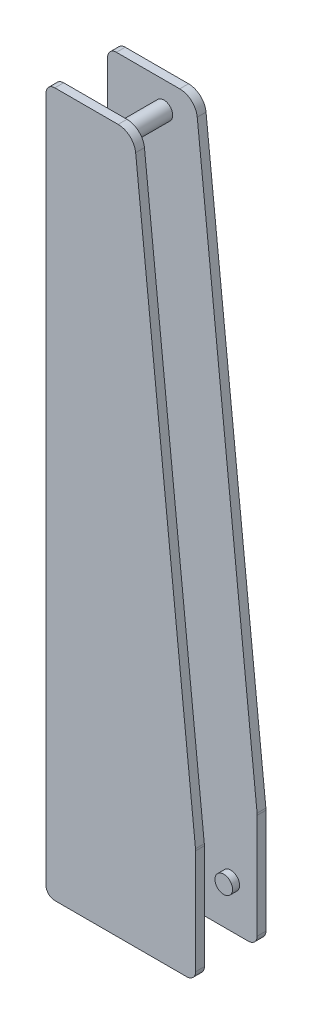
SolidWorks part; units mm, degrees
ref_plane "Front Plane" through (0, 0, 0) normal (0, 0, 1) x (1, 0, 0)
ref_plane "Top Plane" through (0, 0, 0) normal (0, 1, 0) x (1, 0, 0)
ref_plane "Right Plane" through (0, 0, 0) normal (1, 0, 0) x (0, 0, -1)
sketch "Sketch2" plane through (0, 0, 0) normal (0, 0, 1) x (1, 0, 0)
  line L0 (0.9362, 291.0391) -> (34.9459, -34.4819)
  line L1 (-45, 300) -> (-9.0097, 300)
  line L2 (-50, 295) -> (-50, -95)
  line L3 (-45, -100) -> (30, -100)
  line L4 (35, -35.521) -> (35, -95)
  arc A0 (30, -100) -> (35, -95) centre (30, -95) ccw
  arc A1 (-50, -95) -> (-45, -100) centre (-45, -95) ccw
  arc A3 (-45, 300) -> (-50, 295) centre (-45, 295) ccw
  arc A4 (34.9459, -34.4819) -> (35, -35.521) centre (25, -35.521) cw
  arc A5 (0.9362, 291.0391) -> (-9.0097, 300) centre (-9.0097, 290) ccw
  point P10 (35, -35)
  point P17 (0, 300)
  dimension "D5" = 5
  dimension "D8" = 10
  dimension "D1" = 400
  dimension "D2" = 85
  dimension "D3" = 100
  dimension "D4" = 35
  dimension "D6" = 50
  dimension "D7" = 35
extrude "Boss-Extrude1" add sketch "Sketch2" along normal blind 5
sketch "Sketch3" plane through (0, 0, 5) normal (0, 0, 1) x (1, 0, 0)
  circle A0 centre (-18, 285) radius 5
  circle A1 centre (20, -75) radius 5
  dimension "D2" = 10
  dimension "D4" = 10
  dimension "D1" = 285
  dimension "D3" = 75
  dimension "D5" = 20
  dimension "D6" = 18
extrude "Boss-Extrude2" add sketch "Sketch3" along normal blind 30
ref_plane "Plane1" through (0, 0, 35) normal (0, 0, 1) x (1, 0, 0)
sketch "Sketch4" plane through (0, 0, 35) normal (0, 0, 1) x (1, 0, 0)
  line L4 (35, -95) -> (35, -35.521)
  line L5 (-9.0097, 300) -> (-45, 300)
  line L6 (-50, 295) -> (-50, -95)
  line L7 (-45, -100) -> (30, -100)
  line L8 (35, -95) -> (35, -35.521)
  line L9 (-9.0097, 300) -> (-45, 300)
  line L10 (-50, 295) -> (-50, -95)
  line L11 (-45, -100) -> (30, -100)
  line L13 (34.9459, -34.4819) -> (0.9362, 291.0391)
  line L14 (34.9459, -34.4819) -> (0.9362, 291.0391)
  arc A4 (30, -100) -> (35, -95) centre (30, -95) ccw
  arc A5 (35, -35.521) -> (34.9459, -34.4819) centre (25, -35.521) ccw
  arc A6 (-45, 300) -> (-50, 295) centre (-45, 295) ccw
  arc A7 (-50, -95) -> (-45, -100) centre (-45, -95) ccw
  arc A8 (30, -100) -> (35, -95) centre (30, -95) ccw
  arc A10 (-45, 300) -> (-50, 295) centre (-45, 295) ccw
  arc A11 (-50, -95) -> (-45, -100) centre (-45, -95) ccw
  arc A13 (35, -35.521) -> (34.9459, -34.4819) centre (25, -35.521) ccw
  arc A14 (0.9362, 291.0391) -> (-9.0097, 300) centre (-9.0097, 290) ccw
  arc A15 (0.9362, 291.0391) -> (-9.0097, 300) centre (-9.0097, 290) ccw
  dimension "D1" = 0
extrude "Boss-Extrude3" add sketch "Sketch4" along normal blind 5
ref_plane "Plane2" through (0, 0, 15) normal (0, 0, 1) x (1, 0, 0)
ref_plane "Plane3" through (0, 0, 20) normal (0, 0, 1) x (1, 0, 0)
sketch "Sketch5" plane through (0, 0, 20) normal (0, 0, 1) x (1, 0, 0)
  circle A0 centre (20, -75) radius 5 construction
  circle A1 centre (20, -75) radius 5
extrude "Cut-Extrude3" cut sketch "Sketch5" against normal blind 11 and the other way blind 11
